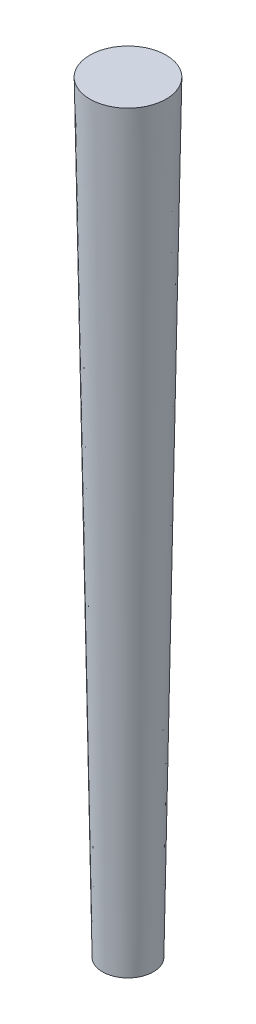
SolidWorks part; units mm, degrees
ref_plane "Front Plane" through (0, 0, 0) normal (0, 0, 1) x (1, 0, 0)
ref_plane "Top Plane" through (0, 0, 0) normal (0, 1, 0) x (1, 0, 0)
ref_plane "Right Plane" through (0, 0, 0) normal (1, 0, 0) x (0, 0, -1)
sketch "Sketch1" plane through (0, 0, 0) normal (0, 0, 1) x (1, 0, 0)
  line L0 (0, 0) -> (2, 0)
  line L1 (2, 0) -> (3, 60)
  line L2 (3, 60) -> (0, 60)
  line L3 (0, 60) -> (0, 0)
  dimension "D1" = 2
  dimension "D2" = 3
  dimension "D3" = 60
revolve "Revolve1" add sketch "Sketch1" angle 360 about L3
